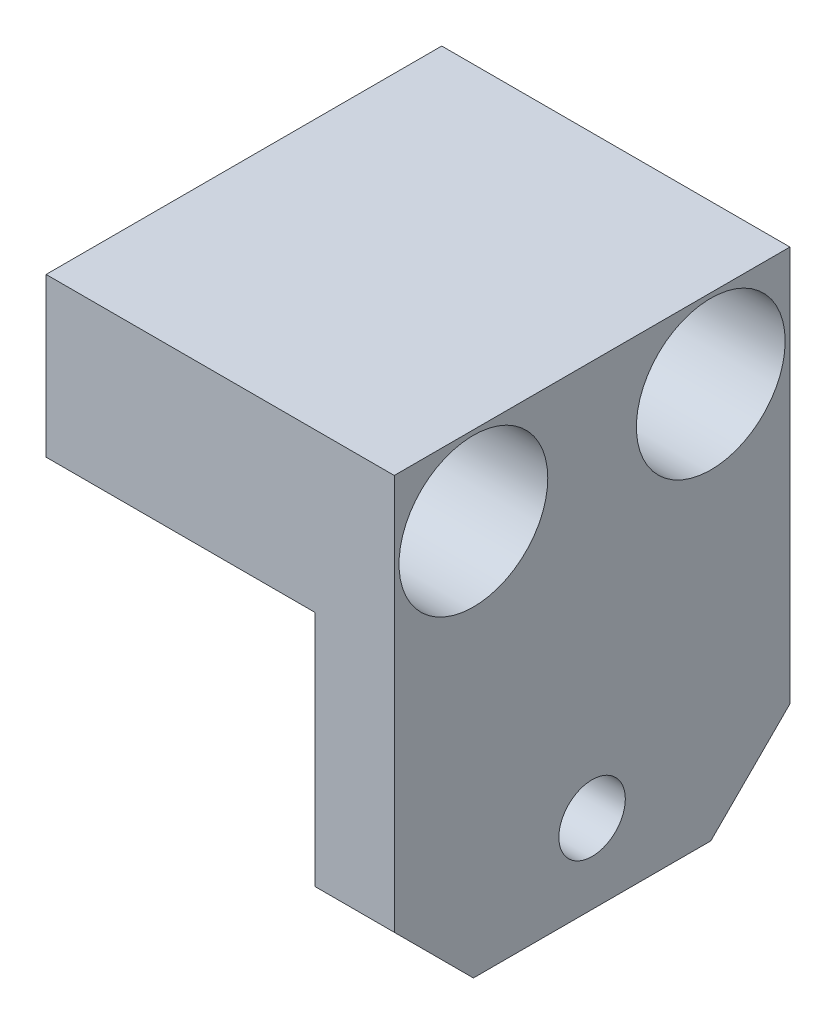
SolidWorks part; units mm, degrees
material "45#"
ref_plane "前视" through (0, 0, 0) normal (0, 0, 1) x (1, 0, 0)
ref_plane "上视" through (0, 0, 0) normal (0, 1, 0) x (1, 0, 0)
ref_plane "右视" through (0, 0, 0) normal (1, 0, 0) x (0, 0, -1)
sketch "草图2" plane through (0, 0, 0) normal (0, 0, 1) x (1, 0, 0)
  line L1 (-11, -15) -> (11, -15)
  line L2 (-11, -15) -> (-11, 15)
  line L3 (-11, 15) -> (11, 15)
  line L4 (11, -15) -> (11, 15)
  line L5 (-11, -15) -> (11, 15) construction
  line L6 (-11, 15) -> (11, -15) construction
  point P0 (0, 0)
  dimension "D1" = 22
  dimension "D2" = 30
extrude "凸台-拉伸1" add sketch "草图2" along normal mid plane 25
sketch "草图3" plane through (0, 0, 12.5) normal (0, 0, 1) x (1, 0, 0)
  line L0 (11, 15) -> (-11, 15) construction
  line L1 (-11, -15) -> (6, -15)
  line L2 (-11, -15) -> (-11, 5)
  line L3 (-11, 5) -> (6, 5)
  line L4 (6, -15) -> (6, 5)
  line L5 (11, -15) -> (11, 15) construction
  dimension "D1" = 10
  dimension "D2" = 5
extrude "切除-拉伸1" cut sketch "草图3" against normal through all
hole_wizard "打孔尺寸根据内六角圆柱头螺钉的类型1" positions "草图5" profile "草图4" counterbore size "M5" standard "Gb" end condition through all
sketch "草图5" plane through (11, 0, 0) normal (1, 0, 0) x (0, 0, -1)
  line L0 (0, 15) -> (0, 10) construction
  line L1 (-12.5, 15) -> (12.5, 15) construction
  line L2 (0, 10) -> (12.5, 10) construction
  line L3 (12.5, 15) -> (12.5, 5) construction
  point P0 (7.5, 10)
  point P16 (-7.5, 10)
  dimension "D1" = 15
sketch "草图4" plane through (11, 10, -7.5) normal (0, 1, 0) x (0, 0, -1)
  line L0 (0, 0) -> (0, 22)
  line L1 (0, 22) -> (2.75, 22)
  line L3 (2.75, 22) -> (2.75, 7)
  line L4 (2.75, 7) -> (4.7, 7)
  line L5 (4.7, 7) -> (4.7, 0)
  line L7 (4.7, 0) -> (0, 0)
  line L11 (0, -6.35) -> (0, 107.95) construction
  dimension "通孔孔直径" = 5.5
  dimension "通孔孔深度" = 22
  dimension "柱形沉头孔直径" = 9.4
  dimension "柱形沉头孔深度" = 7
hole_wizard "M5 螺纹孔1" positions "草图9" profile "草图8" tap size "M5" standard "Gb" end condition through all
sketch "草图9" plane through (11, 0, 0) normal (1, 0, 0) x (0, 0, -1)
  line L1 (12.5, 5) -> (-12.5, 5) construction
  line L2 (0, 15) -> (0, -17.8257) construction
  line L3 (-12.5, 15) -> (12.5, 15) construction
  point P0 (0, -10)
  dimension "D2" = 15
sketch "草图8" plane through (11, -10, 0) normal (0, 1, 0) x (0, 0, -1)
  line L0 (0, 0) -> (0, 22)
  line L1 (0, 22) -> (2.1, 22)
  line L2 (2.1, 22) -> (2.1, 0)
  line L5 (2.1, 0) -> (0, 0)
  line L11 (0, -6.35) -> (0, 107.95) construction
  dimension "通孔螺纹孔钻头直径" = 4.2
  dimension "通孔螺纹孔钻头深度" = 22
cosmetic thread "孔螺蚊线1" parameters "D2"=5
chamfer "倒角1" distance 5 angle 45 2 edges at (8.5, -15, -12.5) (8.5, -15, 12.5)
